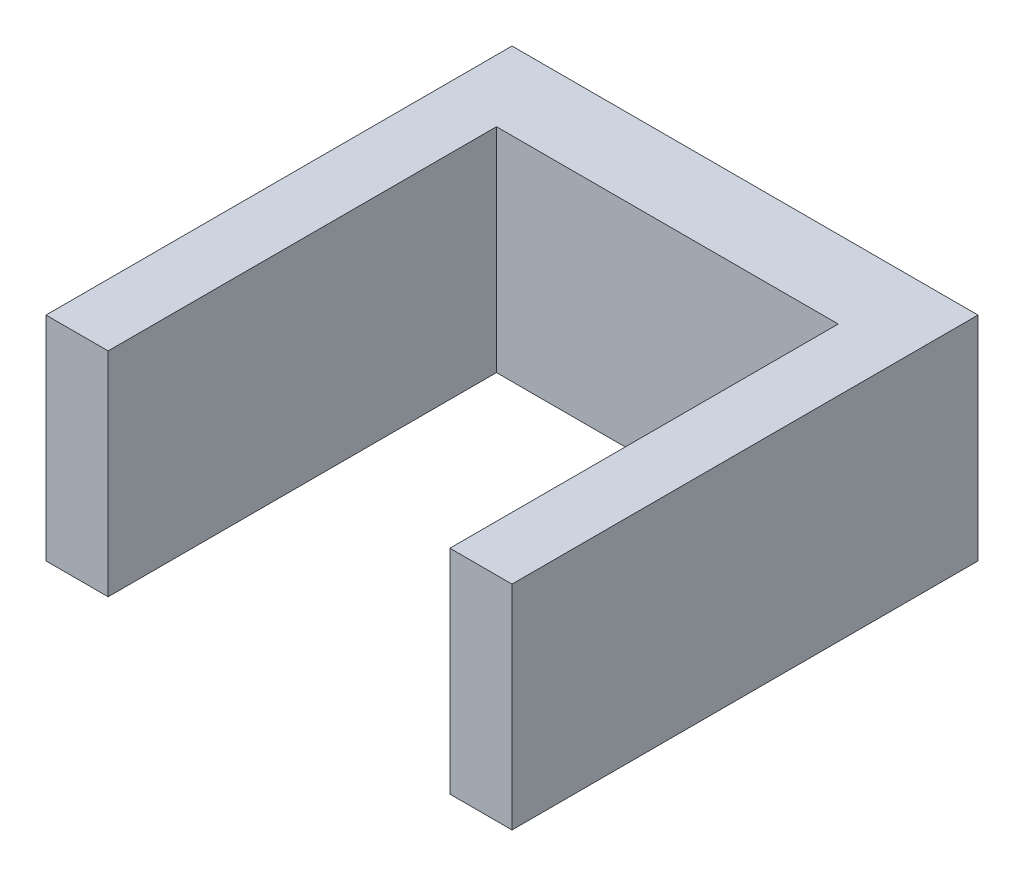
SolidWorks part; units mm, degrees
material "ABS"
ref_plane "Front" through (0, 0, 0) normal (0, 0, 1) x (1, 0, 0)
ref_plane "Top" through (0, 0, 0) normal (0, 1, 0) x (1, 0, 0)
ref_plane "Right" through (0, 0, 0) normal (1, 0, 0) x (0, 0, -1)
sketch "Sketch1" plane through (0, 0, 0) normal (0, 1, 0) x (1, 0, 0)
  line L0 (0, 0) -> (0, 30)
  line L1 (0, 30) -> (30, 30)
  line L2 (30, 30) -> (30, 0)
  line L3 (30, 0) -> (26, 0)
  line L4 (4, 0) -> (4, 25)
  line L5 (4, 25) -> (26, 25)
  line L6 (26, 25) -> (26, 0)
  line L7 (4, 0) -> (0, 0)
  line L8 (4, 25) -> (0, 25) construction
  line L9 (26, 25) -> (30, 25) construction
  dimension "D1" = 22
  dimension "D2" = 30
  dimension "D4" = 5
  dimension "D5" = 25
extrude "Boss-Extrude1" add sketch "Sketch1" along normal blind 13.71
